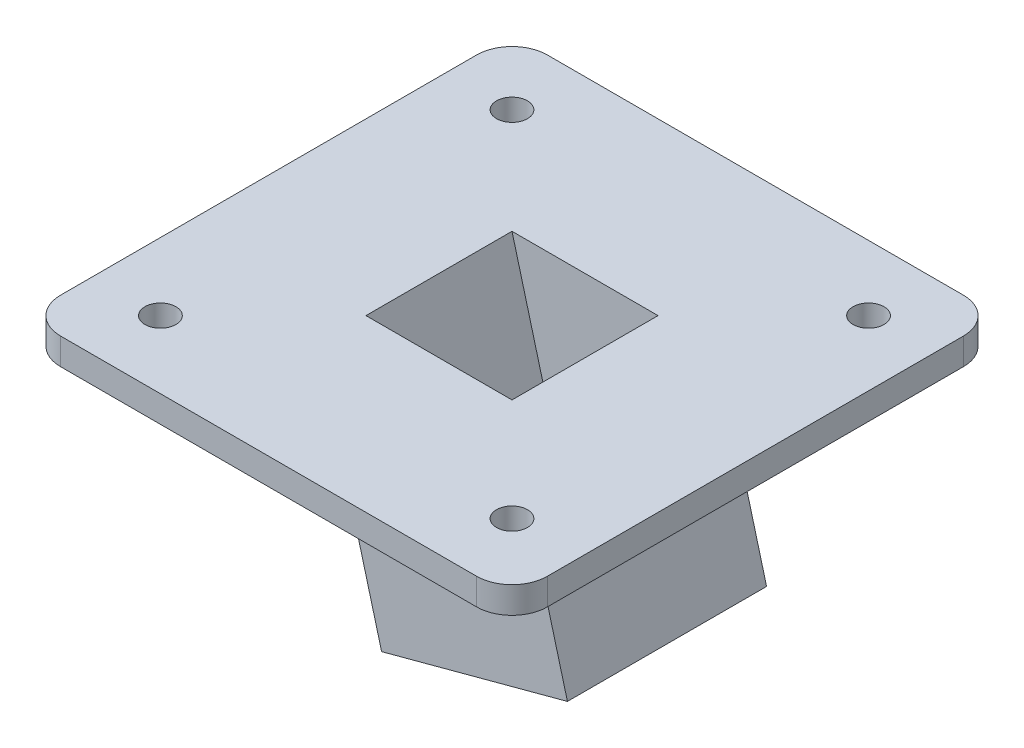
SolidWorks part; units mm, degrees
ref_plane "Front Plane" through (0, 0, 0) normal (0, 0, 1) x (1, 0, 0)
ref_plane "Top Plane" through (0, 0, 0) normal (0, 1, 0) x (1, 0, 0)
ref_plane "Right Plane" through (0, 0, 0) normal (1, 0, 0) x (0, 0, -1)
sketch "Sketch1" plane through (0, 0, 0) normal (0, 1, 0) x (1, 0, 0)
  line L0 (0, 0) -> (0, -12.8421) construction
  line L1 (-27.5, 27.5) -> (27.5, 27.5)
  line L2 (-27.5, 27.5) -> (-27.5, -27.5)
  line L3 (-27.5, -27.5) -> (27.5, -27.5)
  line L4 (27.5, 27.5) -> (27.5, -27.5)
  line L5 (-27.5, 27.5) -> (27.5, -27.5) construction
  line L6 (-27.5, -27.5) -> (27.5, 27.5) construction
  circle A0 centre (20.1404, 20.1404) radius 1.75
  circle A1 centre (-19.8596, -19.8596) radius 1.75
  circle A2 centre (-20.1404, 20.1404) radius 1.75
  circle A3 centre (19.8596, -19.8596) radius 1.75
  point P0 (0, 0)
  dimension "D4" = 3.5
  dimension "D5" = 40
  dimension "D1" = 55
  dimension "D2" = 55
  dimension "D3" = 40
extrude "Boss-Extrude1" add sketch "Sketch1" along normal blind 3
sketch "Sketch2" plane through (0, 3, 0) normal (0, 1, 0) x (1, 0, 0)
  line L0 (27.5, 27.5) -> (-27.5, -27.5) construction
  line L1 (8.25, -8.25) -> (-8.25, -8.25)
  line L2 (11.25, -11.25) -> (-11.25, -11.25)
  line L3 (11.25, -11.25) -> (11.25, 11.25)
  line L4 (11.25, 11.25) -> (-11.25, 11.25)
  line L5 (-11.25, -11.25) -> (-11.25, 11.25)
  line L6 (11.25, -11.25) -> (-11.25, 11.25) construction
  line L7 (11.25, 11.25) -> (-11.25, -11.25) construction
  line L8 (-8.25, -8.25) -> (-8.25, 8.25)
  line L9 (8.25, 8.25) -> (-8.25, 8.25)
  line L10 (8.25, -8.25) -> (8.25, 8.25)
  point P4 (0, 0)
  dimension "D1" = 22.5
  dimension "D2" = 3
sketch "Sketch3" plane through (0, 3, 0) normal (0, 1, 0) x (1, 0, 0)
  line L4 (27.5, -27.5) -> (27.5, 27.5)
  line L5 (27.5, -27.5) -> (27.5, 27.5)
  line L6 (27.5, 27.5) -> (-27.5, 27.5)
  line L7 (27.5, 27.5) -> (-27.5, 27.5)
  line L12 (-27.5, 27.5) -> (-27.5, -27.5)
  line L13 (-27.5, 27.5) -> (-27.5, -27.5)
  line L14 (-27.5, -27.5) -> (27.5, -27.5)
  line L15 (-27.5, -27.5) -> (27.5, -27.5)
  dimension "D1" = 0
sketch "Sketch4" plane through (0, 0, 27.5) normal (0, 0, 1) x (1, 0, 0)
  line L0 (0, 0) -> (-3.1111, 11.6106)
  line L1 (0, 0) -> (0, 12.6705) construction
  dimension "D1" = 15
ref_plane "Plane1" through (0, 0, 27.5) normal (-0.2588, 0.9659, 0) x (0.9659, 0.2588, 0)
ref_plane "Plane2" through (3.4185, -12.7581, 27.5) normal (-0.2588, 0.9659, 0) x (0.9659, 0.2588, 0)
sketch "Sketch7" plane through (3.4185, -12.7581, 27.5) normal (-0.2588, 0.9659, 0) x (0.9659, 0.2588, 0)
  line L4 (-10.0902, 16.25) -> (11.6431, 16.25)
  line L5 (-10.0902, 38.75) -> (-10.0902, 16.25)
  line L6 (11.6431, 38.75) -> (-10.0902, 38.75)
  line L7 (11.6431, 16.25) -> (11.6431, 38.75)
  line L8 (-10.0902, 16.25) -> (11.6431, 16.25)
  line L9 (-10.0902, 38.75) -> (-10.0902, 16.25)
  line L10 (11.6431, 38.75) -> (-10.0902, 38.75)
  line L11 (11.6431, 16.25) -> (11.6431, 38.75)
  line L12 (-7.1924, 19.25) -> (8.7453, 19.25)
  line L13 (-7.1924, 35.75) -> (-7.1924, 19.25)
  line L14 (8.7453, 35.75) -> (-7.1924, 35.75)
  line L15 (8.7453, 19.25) -> (8.7453, 35.75)
  line L16 (-7.1924, 19.25) -> (8.7453, 19.25)
  line L17 (-7.1924, 35.75) -> (-7.1924, 19.25)
  line L18 (8.7453, 35.75) -> (-7.1924, 35.75)
  line L19 (8.7453, 19.25) -> (8.7453, 35.75)
  dimension "D1" = 0
  dimension "D2" = 0
extrude "Boss-Extrude3" add sketch "Sketch7" along normal up to surface and the other way blind 11 up to face at (0, 0, 0)
sketch "Sketch8" plane through (6.2655, -23.3833, 0) normal (0.2588, -0.9659, 0) x (0.9659, 0.2588, 0)
  line L4 (8.7453, -8.25) -> (8.7453, 8.25)
  line L5 (8.7453, 8.25) -> (-7.1924, 8.25)
  line L6 (-7.1924, 8.25) -> (-7.1924, -8.25)
  line L7 (-7.1924, -8.25) -> (8.7453, -8.25)
  line L8 (8.7453, -8.25) -> (8.7453, 8.25)
  line L9 (8.7453, 8.25) -> (-7.1924, 8.25)
  line L10 (-7.1924, 8.25) -> (-7.1924, -8.25)
  line L11 (-7.1924, -8.25) -> (8.7453, -8.25)
  dimension "D1" = 0
extrude "Cut-Extrude2" cut sketch "Sketch8" against normal blind 30
fillet "Fillet3" radius 4 8 edges at (27.5, 1.5, 27.5) (27.5, 1.5, -27.5) (-27.5, 1.5, -27.5) (-27.5, 1.5, 27.5) (0.8038, 0, -11.25) (12.0538, 0, 0) (0.8038, 0, 11.25) (-10.4462, 0, 0)
